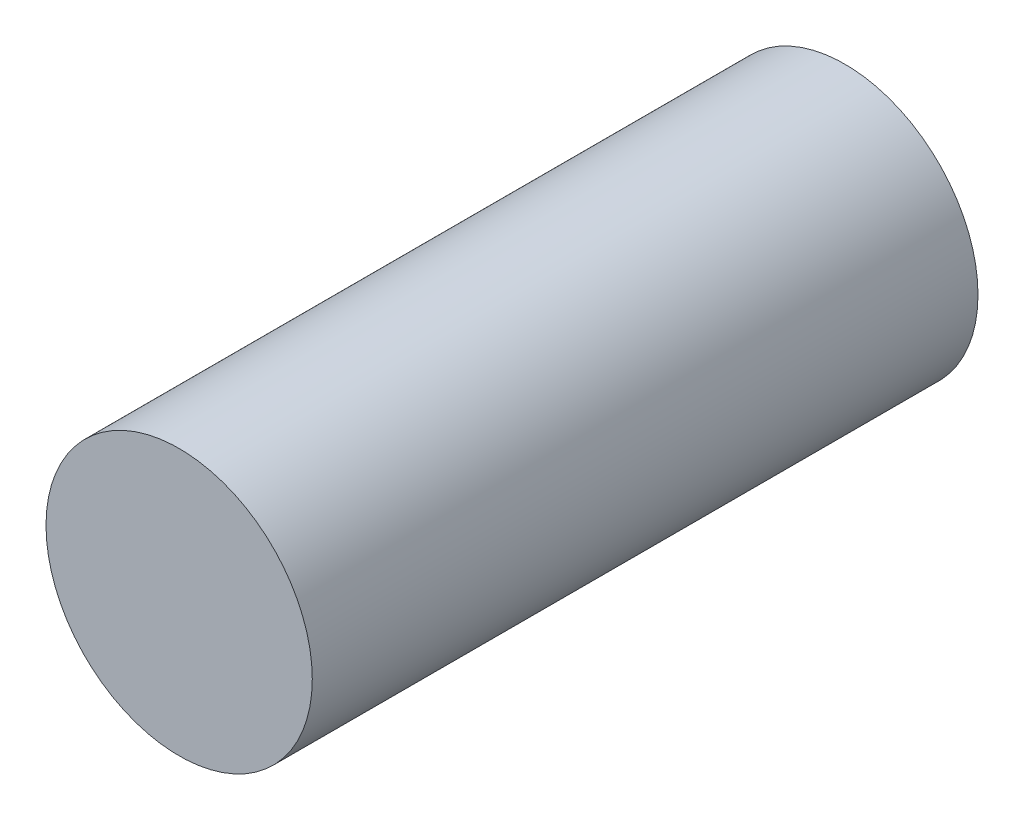
SolidWorks part; units mm, degrees
ref_plane "Front Plane" through (0, 0, 0) normal (0, 0, 1) x (1, 0, 0)
ref_plane "Top Plane" through (0, 0, 0) normal (0, 1, 0) x (1, 0, 0)
ref_plane "Right Plane" through (0, 0, 0) normal (1, 0, 0) x (0, 0, -1)
other "Configuration Table"
sketch "Sketch1" plane through (0, 0, 0) normal (0, 0, 1) x (1, 0, 0)
  circle A0 centre (300, 1744) radius 4
extrude "TOPPING_kat1_kapak_pimi_D8_1" add sketch "Sketch1" against normal blind 20 from offset 40 separate body
